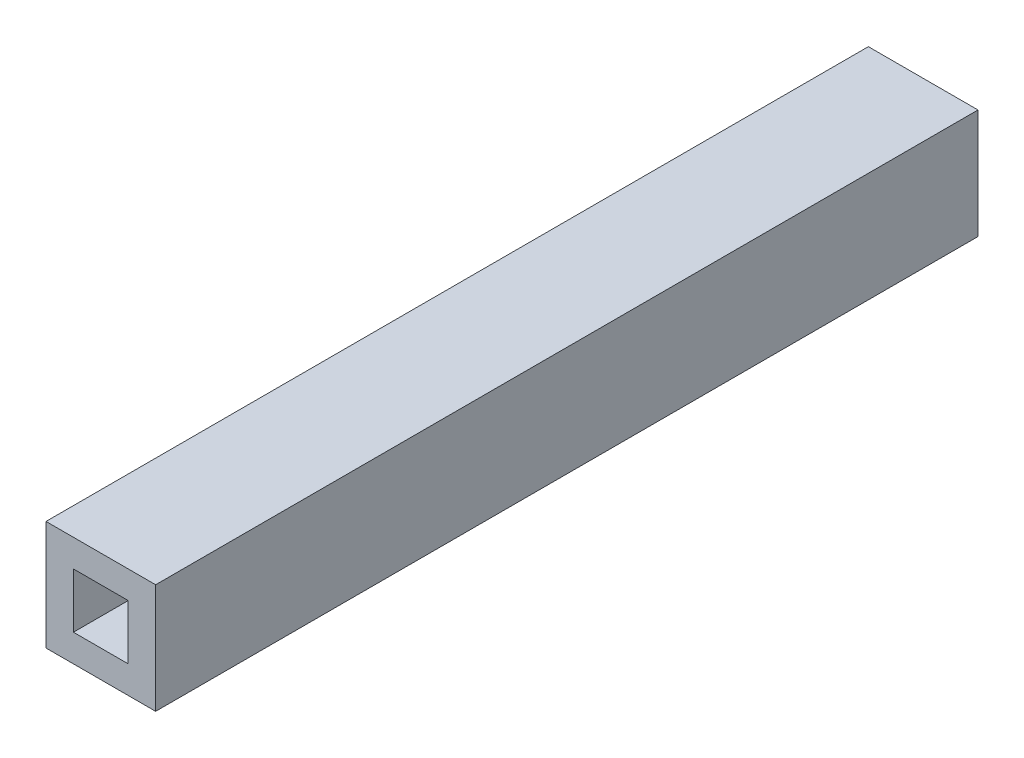
SolidWorks part; units mm, degrees
material "6063-O"
ref_plane "Front Plane" through (0, 0, 0) normal (0, 0, 1) x (1, 0, 0)
ref_plane "Top Plane" through (0, 0, 0) normal (0, 1, 0) x (1, 0, 0)
ref_plane "Right Plane" through (0, 0, 0) normal (1, 0, 0) x (0, 0, -1)
sketch "Sketch1" plane through (0, 0, 0) normal (0, 0, 1) x (1, 0, 0)
  line L1 (-10, -10) -> (10, -10)
  line L2 (-10, -10) -> (-10, 10)
  line L3 (-10, 10) -> (10, 10)
  line L4 (10, -10) -> (10, 10)
  line L5 (-10, -10) -> (10, 10) construction
  line L6 (-10, 10) -> (10, -10) construction
  point P0 (0, 0)
  dimension "D1" = 20
extrude "Extrude-Thin1" add sketch "Sketch1" along normal blind 150 thin thin type one direction reverse wall 5
